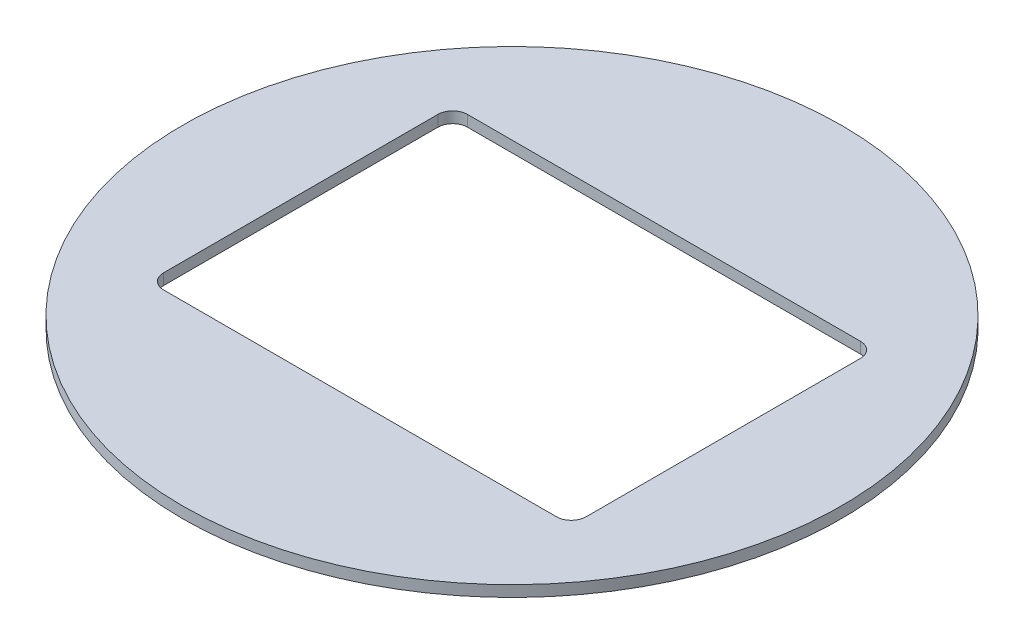
SolidWorks part; units mm, degrees
ref_plane "Front Plane" through (0, 0, 0) normal (0, 0, 1) x (1, 0, 0)
ref_plane "Top Plane" through (0, 0, 0) normal (0, 1, 0) x (1, 0, 0)
ref_plane "Right Plane" through (0, 0, 0) normal (1, 0, 0) x (0, 0, -1)
sketch "Sketch1" plane through (0, 0, 0) normal (0, 1, 0) x (1, 0, 0)
  circle A0 centre (0, 0) radius 88.9
  dimension "D1" = 177.8
extrude "Boss-Extrude1" add sketch "Sketch1" along normal blind 3
extrude "Cut-Extrude2" cut sketch "Sketch3" against normal blind 3
sketch "Sketch3" plane through (0, 0, 0) normal (0, -1, 0) x (1, 0, 0)
  line L1 (53, -41) -> (-53, -41)
  line L2 (57, -37) -> (57, 37)
  line L3 (53, 41) -> (-53, 41)
  line L4 (-57, -37) -> (-57, 37)
  line L5 (57, -41) -> (-57, 41) construction
  line L6 (57, 41) -> (-57, -41) construction
  arc A0 (-53, 41) -> (-57, 37) centre (-53, 37) ccw
  arc A1 (-53, -41) -> (-57, -37) centre (-53, -37) cw
  arc A2 (57, 37) -> (53, 41) centre (53, 37) ccw
  arc A3 (53, -41) -> (57, -37) centre (53, -37) ccw
  point P0 (0, 0)
